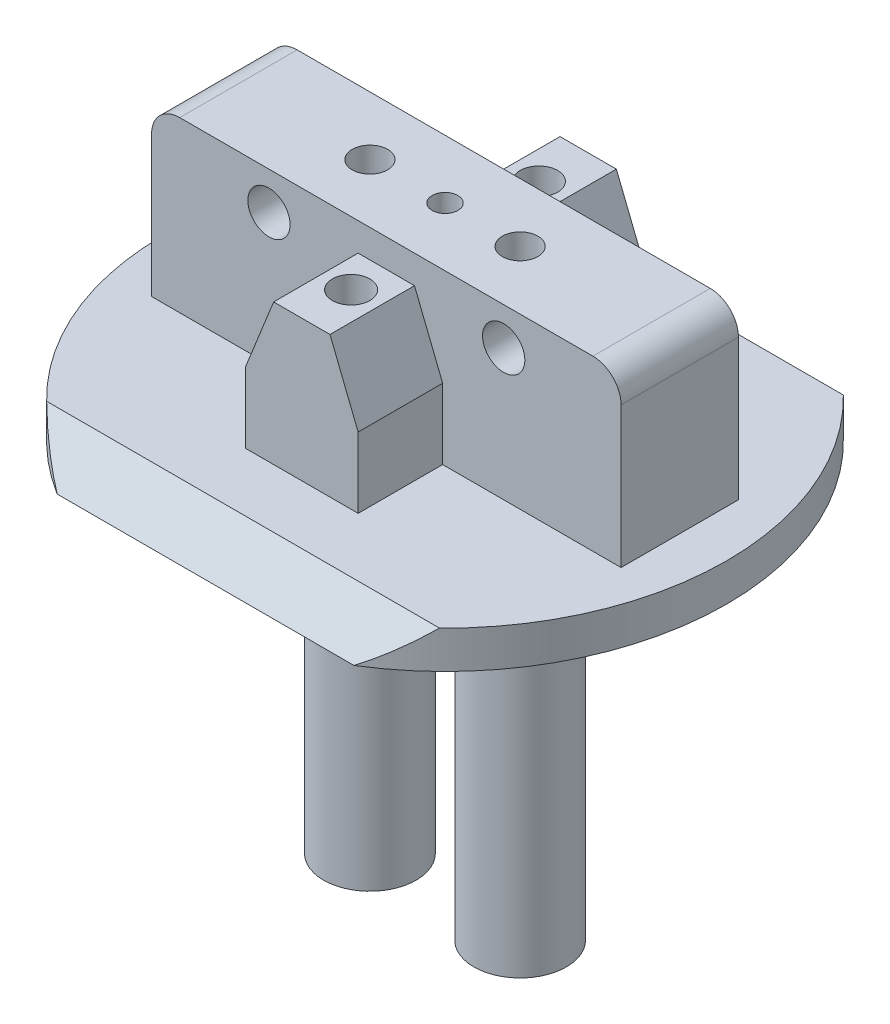
SolidWorks part; units mm, degrees
ref_plane "Front Plane" through (0, 0, 0) normal (0, 0, 1) x (1, 0, 0)
ref_plane "Top Plane" through (0, 0, 0) normal (0, 1, 0) x (1, 0, 0)
ref_plane "Right Plane" through (0, 0, 0) normal (1, 0, 0) x (0, 0, -1)
sketch "Sketch1" plane through (0, 0, 0) normal (0, 1, 0) x (1, 0, 0)
  circle A0 centre (0, 0) radius 30
extrude "Boss-Extrude1" add sketch "Sketch1" along normal blind 4
sketch "Sketch2" plane through (0, 0, 0) normal (1, 0, 0) x (0, 0, -1)
  line L0 (0, 4) -> (21.5, 4)
  line L1 (30, 4) -> (-30, 4) construction
  line L3 (0, 4) -> (-21.5, 4)
  line L5 (0, 4) -> (0, 19.5) construction
  line L6 (-9, 16.5) -> (-21.5, 4)
  line L7 (-9, 16.5) -> (9, 16.5)
  line L9 (9, 16.5) -> (21.5, 4)
  dimension "D1" = 12.5
  dimension "D2" = 45
  dimension "D3" = 21.5
  dimension "D4" = 21.5
  dimension "D5" = 45
sketch "Sketch3" plane through (0, 4, 0) normal (0, 1, 0) x (1, 0, 0)
  circle A0 centre (0, 0) radius 21.5
  dimension "D1" = 43
extrude "Boss-Extrude2" add sketch "Sketch2" along normal up to surface and the other way up to surface up to face at (0, 4, 30) other way up to face at (0, 4, 30)
ref_plane "Plane1" through (0, 12.75, -12.75) normal (0, 0.7071, -0.7071) x (1, 0, 0)
other "SurfaceCut1"
ref_plane "Plane2" through (0, 12.75, 12.75) normal (0, 0.7071, 0.7071) x (1, 0, 0)
other "SurfaceCut2"
extrude "Cut-Extrude2" cut sketch "Sketch3" against normal up to surface (12.5 mm away) flip side to cut contours A0
sketch "Sketch5" plane through (0, 0, 0) normal (0, -1, 0) x (-1, 0, 0)
  line L0 (0, 0) -> (0, -6)
  line L1 (0, -6) -> (-17.5, -6)
  line L2 (-17.5, -6) -> (-17.5, 6)
  line L3 (-17.5, 6) -> (17.5, 6)
  line L4 (17.5, 6) -> (17.5, -6)
  line L5 (17.5, -6) -> (0, -6)
  circle A0 centre (0, 0) radius 6
  circle A1 centre (0, 0) radius 3.5
  dimension "D1" = 12
  dimension "D2" = 7
  dimension "D3" = 12
  dimension "D4" = 6
  dimension "D5" = 35
  dimension "D6" = 17.5
extrude "Boss-Extrude3" add sketch "Sketch5" along normal blind 18 contours L1 L2 L3 L4 L5
sketch "Sketch6" plane through (0, 0, 0) normal (0, -1, 0) x (1, 0, 0)
  line L0 (0, 6) -> (0, 15) construction
  line L1 (-17.5, 6) -> (17.5, 6) construction
  line L2 (0, 15) -> (7, 15)
  line L3 (7, 15) -> (7, 6)
  line L4 (-17.5, 6) -> (17.5, 6) construction
  line L5 (7, 6) -> (-7, 6)
  line L6 (-7, 6) -> (-7, 15)
  line L7 (-7, 15) -> (0, 15)
  dimension "D1" = 14
  dimension "D2" = 9
extrude "Boss-Extrude4" add sketch "Sketch6" along normal blind 15 contours L7 L2 L3 L5 L6
sketch "Sketch7" plane through (0, 0, 0) normal (0, -1, 0) x (1, 0, 0)
  line L0 (0, -6) -> (0, -15) construction
  line L1 (17.5, -6) -> (-17.5, -6) construction
  line L2 (0, -15) -> (7, -15)
  line L3 (7, -15) -> (7, -6)
  line L4 (7, -6) -> (-7, -6)
  line L7 (-7, -6) -> (-7, -15)
  line L8 (-7, -15) -> (0, -15)
  dimension "D1" = 9
  dimension "D2" = 14
extrude "Boss-Extrude5" add sketch "Sketch7" along normal blind 15
sketch "Sketch8" plane through (0, 0, 0) normal (0, 0, 1) x (1, 0, 0)
  line L0 (0, 0) -> (12.5, 0) construction
  line L1 (12.5, 0) -> (12.5, -12.5) construction
  line L2 (12.5, -12.5) -> (-12.5, -12.5) construction
  line L3 (-12.5, -12.5) -> (-12.5, 0) construction
  line L4 (-12.5, 0) -> (0, 0) construction
  circle A0 centre (-12.5, -12.5) radius 2
  circle A1 centre (12.5, -12.5) radius 2
  dimension "D4" = 4
  dimension "D5" = 4
  dimension "D1" = 12.5
  dimension "D2" = 25
  dimension "D3" = 12.5
extrude "Cut-Extrude3" cut sketch "Sketch8" against normal through all both and the other way through all contours A0 | A1
ref_plane "Plane3" through (0, -18, 0) normal (0, -1, 0) x (-1, 0, 0)
ref_plane "Plane4" through (10.366, -9.6749, -8.0624) normal (0.6355, -0.5931, -0.4943) x (-0.3613, 0.3373, -0.8693)
ref_plane "Plane5" through (-10.366, -9.6749, -8.0624) normal (0.6355, 0.5931, 0.4943) x (0.3613, 0.3373, -0.8693)
ref_plane "Plane6" through (10.366, -9.6749, 8.0624) normal (-0.6355, 0.5931, -0.4943) x (-0.3613, 0.3373, 0.8693)
ref_plane "Plane7" through (-10.366, -9.6749, 8.0624) normal (0.6355, 0.5931, -0.4943) x (-0.3613, -0.3373, -0.8693)
ref_plane "Plane9" through (0, 0, 6) normal (0, 0, 1) x (1, 0, 0)
sketch "Sketch16" plane through (0, 0, 6) normal (0, 0, 1) x (1, 0, 0)
  line L0 (17.5, -18) -> (17.5, -14.5)
  line L1 (-6.6, -18) -> (6.6, -18) construction
  line L2 (17.5, -18) -> (17.5, 0) construction
  line L3 (17.5, -18) -> (14, -18)
  line L4 (17.5, -14.5) -> (14, -18)
  line L5 (-17.5, -18) -> (-14, -18)
  line L6 (-17.5, -18) -> (-17.5, 0) construction
  line L7 (-14, -18) -> (-17.5, -14.5)
  line L8 (-17.5, -14.5) -> (-17.5, -18)
  dimension "D2" = 3.5
extrude "Cut-Extrude8" cut sketch "Sketch16" against normal through all both and the other way through all
sketch "Sketch17" plane through (10.366, -9.6749, -8.0624) normal (0.6355, -0.5931, -0.4943) x (-0.3613, 0.3373, -0.8693)
  line L0 (-2.3725, -6.1896) -> (7.9806, -0.7067)
  line L1 (5.4512, -6.1896) -> (10.5101, 4.7762) construction
  line L2 (7.9806, -0.7067) -> (7.9806, -10.9658)
  line L3 (10.5101, -15.7421) -> (5.4512, -6.1896) construction
  line L4 (7.9806, -10.9658) -> (-2.3725, -6.1896)
extrude "Cut-Extrude9" cut sketch "Sketch17" along normal through all
sketch "Sketch19" plane through (-10.366, -9.6749, -8.0624) normal (0.6355, 0.5931, 0.4943) x (0.3613, 0.3373, -0.8693)
  line L0 (-2.3725, -6.1896) -> (7.9806, -10.9658)
  line L1 (7.9806, -10.9658) -> (7.9806, -0.7067)
  line L2 (5.4512, -6.1896) -> (10.5101, 4.7762) construction
  line L3 (7.9806, -0.7067) -> (-2.3725, -6.1896)
extrude "Cut-Extrude11" cut sketch "Sketch19" against normal blind 20 contours L3 L0 L1
sketch "Sketch20" plane through (-10.366, -9.6749, 8.0624) normal (0.6355, 0.5931, -0.4943) x (-0.3613, -0.3373, -0.8693)
  line L0 (2.3725, -6.1896) -> (-7.9806, -0.7067)
  line L1 (-5.4512, -6.1896) -> (-10.5101, 4.7762) construction
  line L2 (-7.9806, -0.7067) -> (-7.9806, -10.9658)
  line L3 (-5.4512, -6.1896) -> (-10.5101, -15.7421) construction
  line L4 (-7.9806, -10.9658) -> (2.3725, -6.1896)
extrude "Cut-Extrude12" cut sketch "Sketch20" against normal blind 20
sketch "Sketch21" plane through (10.366, -9.6749, 8.0624) normal (-0.6355, 0.5931, -0.4943) x (-0.3613, 0.3373, 0.8693)
  line L0 (-2.3725, -6.1896) -> (7.9806, -0.7067)
  line L1 (5.4512, -6.1896) -> (10.5101, 4.7762) construction
  line L2 (7.9806, -0.7067) -> (7.9806, -10.9658)
  line L3 (7.9806, -10.9658) -> (-2.3725, -6.1896)
extrude "Cut-Extrude13" cut sketch "Sketch21" against normal blind 20 contours L0 L2 L3
ref_plane "Plane10" through (0, 16.5, 0) normal (0, 1, 0) x (1, 0, 0)
sketch "Sketch25" plane through (0, 0, 0) normal (0, 0, 1) x (1, 0, 0)
  line L1 (-33.0377, 0) -> (33.0377, 0)
  line L2 (-33.0377, 0) -> (-33.0377, -20.1422)
  line L3 (-33.0377, -20.1422) -> (33.0377, -20.1422)
  line L4 (33.0377, 0) -> (33.0377, -20.1422)
  dimension "D1" = 20.1422
  dimension "D2" = 66.0754
extrude "Cut-Extrude14" cut sketch "Sketch25" along normal through all both and the other way through all
sketch "Sketch26" plane through (0, 16.5, 0) normal (0, 1, 0) x (1, 0, 0)
  line L0 (-12.1, 0) -> (12.1, 0) construction
  circle A0 centre (-8, 0) radius 5
  circle A2 centre (8, 0) radius 5
  dimension "D1" = 10
  dimension "D2" = 10
  dimension "D3" = 8
  dimension "D4" = 8
sketch "Sketch27" plane through (0, 16.5, 0) normal (0, 1, 0) x (1, 0, 0)
  line L0 (0, -9.075) -> (0, 9.075) construction
  circle A0 centre (0, 0) radius 1.375
  dimension "D1" = 2.75
  dimension "D2" = 0
extrude "Cut-Extrude16" cut sketch "Sketch27" against normal blind 30
sketch "Sketch28" plane through (0, 0, 0) normal (0, -1, 0) x (1, 0, 0)
  line L0 (0, -9.075) -> (0, 9.075) construction
  line L1 (9.075, 0) -> (-9.075, 0) construction
  circle A0 centre (0, -15) radius 5
  circle A1 centre (22, 0) radius 5
  circle A2 centre (0, 15) radius 5
  circle A3 centre (-22, 0) radius 5
  circle A4 centre (-14, 12) radius 5
  circle A5 centre (14, 12) radius 5
  circle A6 centre (14, -12) radius 5
  circle A7 centre (-14, -12) radius 5
  dimension "D1" = 10
  dimension "D2" = 10
  dimension "D3" = 10
  dimension "D4" = 10
  dimension "D5" = 10
  dimension "D6" = 10
  dimension "D7" = 10
  dimension "D10" = 10
  dimension "D11" = 15
  dimension "D8" = 22
  dimension "D9" = 22
  dimension "D12" = 15
  dimension "D13" = 14
  dimension "D14" = 14
  dimension "D15" = 14
  dimension "D16" = 14
  dimension "D17" = 12
  dimension "D18" = 12
  dimension "D19" = 12
  dimension "D20" = 12
extrude "Cut-Extrude17" cut sketch "Sketch28" against normal blind 3
sketch "Sketch29" plane through (0, 0, 0) normal (1, 0, 0) x (0, 0, -1)
  line L0 (-10.55, 14.95) -> (-14.95, 10.55) construction
  line L1 (-21.5, 4) -> (21.9126, 4)
  line L2 (-21.5, 4) -> (-21.5, 17.3262)
  line L3 (-21.5, 17.3262) -> (21.9126, 17.3262)
  line L4 (21.9126, 4) -> (21.9126, 17.3262)
  line L5 (21.5, 4) -> (-21.5, 4) construction
extrude "Cut-Extrude18" cut sketch "Sketch29" against normal through all both and the other way through all
sketch "Sketch32" plane through (0, 4, 0) normal (0, 1, 0) x (1, 0, 0)
  line L1 (-25, 6.25) -> (25, 6.25)
  line L2 (-25, 6.25) -> (-25, -6.25)
  line L3 (-25, -6.25) -> (25, -6.25)
  line L4 (25, 6.25) -> (25, -6.25)
  line L5 (-25, 6.25) -> (25, -6.25) construction
  line L6 (-25, -6.25) -> (25, 6.25) construction
  point P0 (0, 0)
  dimension "D1" = 12.5
  dimension "D2" = 50
extrude "Boss-Extrude6" add sketch "Sketch32" along normal blind 18
sketch "Sketch35" plane through (0, 0, -6.25) normal (0, 0, -1) x (-1, 0, 0)
  line L0 (-20.9225, 4) -> (20.9225, 4) construction
  line L1 (-6, 4) -> (6, 4)
  line L2 (-6, 4) -> (-6, 19)
  line L3 (-6, 19) -> (6, 19)
  line L4 (6, 4) -> (6, 19)
  line L5 (0, 9.075) -> (0, -9.075) construction
  dimension "D1" = 12
  dimension "D2" = 15
  dimension "D3" = 6
extrude "Boss-Extrude7" add sketch "Sketch35" along normal blind 9
sketch "Sketch36" plane through (0, 19, 0) normal (0, 1, 0) x (1, 0, 0)
  line L0 (0, -9.075) -> (0, 9.075) construction
  circle A0 centre (0, 10) radius 2
  dimension "D1" = 4
  dimension "D2" = 10
sketch "Sketch37" plane through (0, 0, -6.25) normal (0, 0, -1) x (-1, 0, 0)
  line L0 (0, 12.1) -> (0, -12.1) construction
  line L3 (-20.9225, 4) -> (20.9225, 4) construction
  line L4 (-6, 4) -> (6, 4) construction
  circle A0 centre (-12.5, 18) radius 2.25
  circle A1 centre (12.5, 18) radius 2.25
  dimension "D5" = 4.5
  dimension "D6" = 4.5
  dimension "D1" = 12.5
  dimension "D2" = 12.5
  dimension "D3" = 14
  dimension "D4" = 14
extrude "Cut-Extrude19" cut sketch "Sketch37" against normal through all both and the other way through all
extrude "Cut-Extrude20" cut sketch "Sketch36" against normal blind 15
sketch "Sketch39" plane through (0, 0, 6.25) normal (0, 0, 1) x (1, 0, 0)
  line L0 (-25, 4) -> (25, 4) construction
  line L1 (-6, 4) -> (6, 4)
  line L2 (-6, 4) -> (-6, 19)
  line L3 (-6, 19) -> (6, 19)
  line L4 (6, 4) -> (6, 19)
  line L5 (0, -12.1) -> (0, 12.1) construction
  dimension "D1" = 12
  dimension "D2" = 6
  dimension "D3" = 15
extrude "Boss-Extrude8" add sketch "Sketch39" along normal blind 9
sketch "Sketch40" plane through (0, 19, 0) normal (0, 1, 0) x (1, 0, 0)
  line L0 (0, -12.1) -> (0, 12.1) construction
  circle A0 centre (0, -10) radius 2
  dimension "D1" = 4
  dimension "D2" = 10
extrude "Cut-Extrude21" cut sketch "Sketch40" against normal blind 15
fillet "Fillet1" radius 3 1 edges at (25, 22, 0)
fillet "Fillet2" radius 3 1 edges at (-25, 22, 0)
sketch "Sketch44" plane through (0, 4, 0) normal (0, -1, 0) x (1, 0, 0)
  circle A0 centre (0, 0) radius 1.375
  dimension "D1" = 2.75
extrude "Cut-Extrude24" cut sketch "Sketch44" against normal blind 20
sketch "Sketch45" plane through (0, 0, 0) normal (0, -1, 0) x (1, 0, 0)
  circle A0 centre (-8, 0) radius 4.925
  circle A1 centre (8, 0) radius 4.925
  dimension "D1" = 9.85
  dimension "D2" = 9.85
extrude "Boss-Extrude9" add sketch "Sketch45" along normal blind 42
sketch "Sketch46" plane through (0, -42, 0) normal (0, -1, 0) x (1, 0, 0)
  circle A0 centre (-8, 0) radius 1.8923
  dimension "D1" = 3.7846
extrude "Cut-Extrude25" cut sketch "Sketch46" against normal blind 76.2
sketch "Sketch47" plane through (0, -42, 0) normal (0, -1, 0) x (1, 0, 0)
  circle A0 centre (8, 0) radius 1.8923
  dimension "D1" = 3.7846
extrude "Cut-Extrude26" cut sketch "Sketch47" against normal blind 76.2
sketch "Sketch58" plane through (0, 0, -15.25) normal (0, 0, -1) x (-1, 0, 0)
  line L0 (6, 19) -> (6, 11.5)
  line L1 (6, 4) -> (6, 19) construction
  line L2 (6, 11.5) -> (3, 19)
  line L3 (6, 19) -> (-6, 19) construction
  line L4 (3, 19) -> (6, 19)
  dimension "D1" = 3
extrude "Cut-Extrude32" cut sketch "Sketch58" against normal up to surface (9 mm away) up to face at (14.75, 18, -6.25)
sketch "Sketch59" plane through (0, 0, -15.25) normal (0, 0, -1) x (-1, 0, 0)
  line L0 (-6, 19) -> (-6, 11.5)
  line L1 (-6, 19) -> (-6, 4) construction
  line L2 (-6, 11.5) -> (-3, 19)
  line L3 (3, 19) -> (-6, 19) construction
  line L4 (-3, 19) -> (-6, 19)
  dimension "D1" = 3
extrude "Cut-Extrude33" cut sketch "Sketch59" against normal up to surface (9 mm away) up to face at (14.75, 18, -6.25)
sketch "Sketch60" plane through (0, 0, 15.25) normal (0, 0, 1) x (1, 0, 0)
  line L0 (6, 11.5) -> (6, 19)
  line L1 (6, 4) -> (6, 19) construction
  line L2 (6, 11.5) -> (3, 19)
  line L3 (6, 19) -> (-6, 19) construction
  line L4 (3, 19) -> (6, 19)
  dimension "D1" = 3
extrude "Cut-Extrude34" cut sketch "Sketch60" against normal up to surface (9 mm away) up to face at (-14.75, 18, 6.25)
sketch "Sketch61" plane through (0, 0, 15.25) normal (0, 0, 1) x (1, 0, 0)
  line L0 (-6, 19) -> (-6, 11.5)
  line L1 (-6, 19) -> (-6, 4) construction
  line L2 (-6, 11.5) -> (-3, 19)
  line L3 (3, 19) -> (-6, 19) construction
  line L4 (-3, 19) -> (-6, 19)
  dimension "D1" = 3
extrude "Cut-Extrude35" cut sketch "Sketch61" against normal up to surface (9 mm away) up to face at (-14.75, 18, 6.25)
